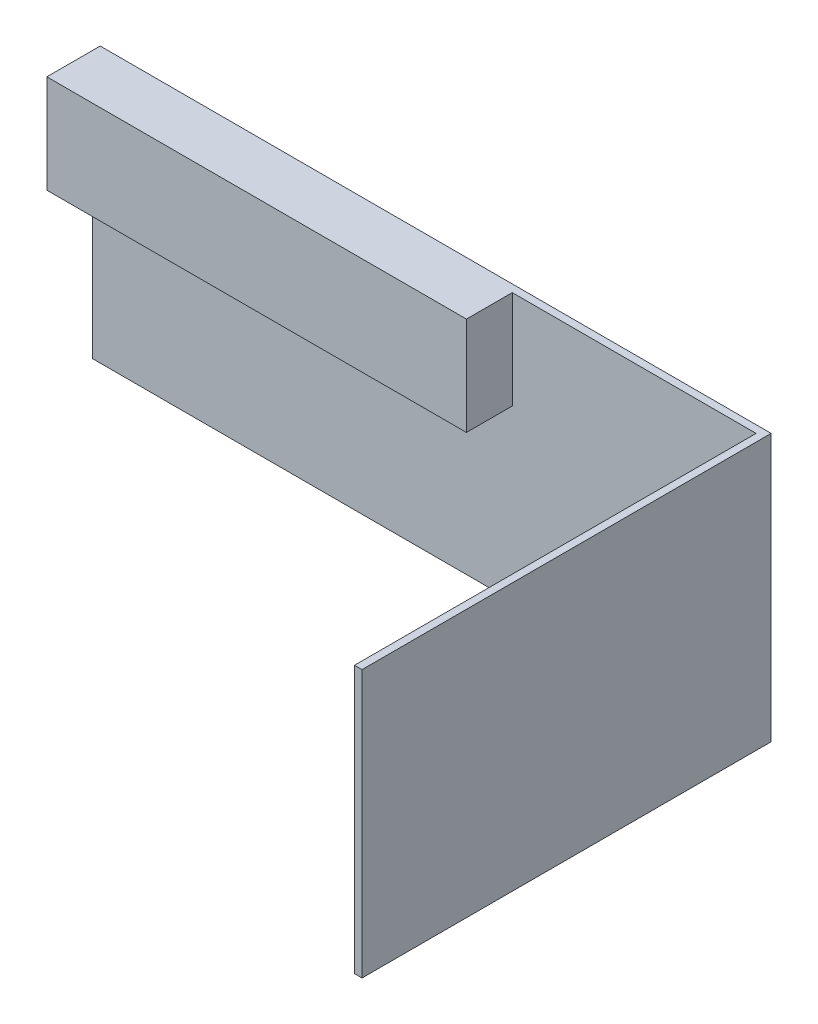
SolidWorks part; units mm, degrees
ref_plane "前视基准面" through (0, 0, 0) normal (0, 0, 1) x (1, 0, 0)
ref_plane "上视基准面" through (0, 0, 0) normal (0, 1, 0) x (1, 0, 0)
ref_plane "右视基准面" through (0, 0, 0) normal (1, 0, 0) x (0, 0, -1)
sketch "草图1" plane through (0, 0, 0) normal (0, 0, 1) x (1, 0, 0)
  line L1 (-21.7772, 5.5523) -> (-1.2772, 5.5523)
  line L2 (-21.7772, 5.5523) -> (-21.7772, -2.6077)
  line L3 (-21.7772, -2.6077) -> (-1.2772, -2.6077)
  line L4 (-1.2772, 5.5523) -> (-1.2772, -2.6077)
  dimension "D1" = 8.16
  dimension "D2" = 20.5
extrude "凸台-拉伸1" add sketch "草图1" along normal blind 0.23
sketch "草图2" plane through (0, 0, 0.23) normal (0, 0, 1) x (1, 0, 0)
  line L1 (-21.7772, 5.5523) -> (-8.9572, 5.5523)
  line L2 (-21.7772, 5.5523) -> (-21.7772, 2.5523)
  line L3 (-21.7772, 2.5523) -> (-8.9572, 2.5523)
  line L4 (-8.9572, 5.5523) -> (-8.9572, 2.5523)
  dimension "D1" = 3
  dimension "D2" = 12.82
extrude "凸台-拉伸2" add sketch "草图2" along normal blind 1.4
sketch "草图3" plane through (0, 0, 0.23) normal (0, 0, 1) x (1, 0, 0)
  line L5 (-1.2772, 5.5523) -> (-8.9572, 5.5523) construction
  line L6 (-1.5072, 5.5523) -> (-1.2772, 5.5523)
  line L7 (-1.5072, 5.5523) -> (-1.5072, -2.6077)
  line L8 (-1.5072, -2.6077) -> (-1.2772, -2.6077)
  line L9 (-1.2772, 5.5523) -> (-1.2772, -2.6077)
  line L10 (-21.7772, -2.6077) -> (-1.2772, -2.6077) construction
  line L12 (-21.7772, 2.5523) -> (-21.7772, -2.6077) construction
  dimension "D1" = 0.23
  dimension "D2" = 20.5
extrude "凸台-拉伸3" add sketch "草图3" along normal blind 12.27
